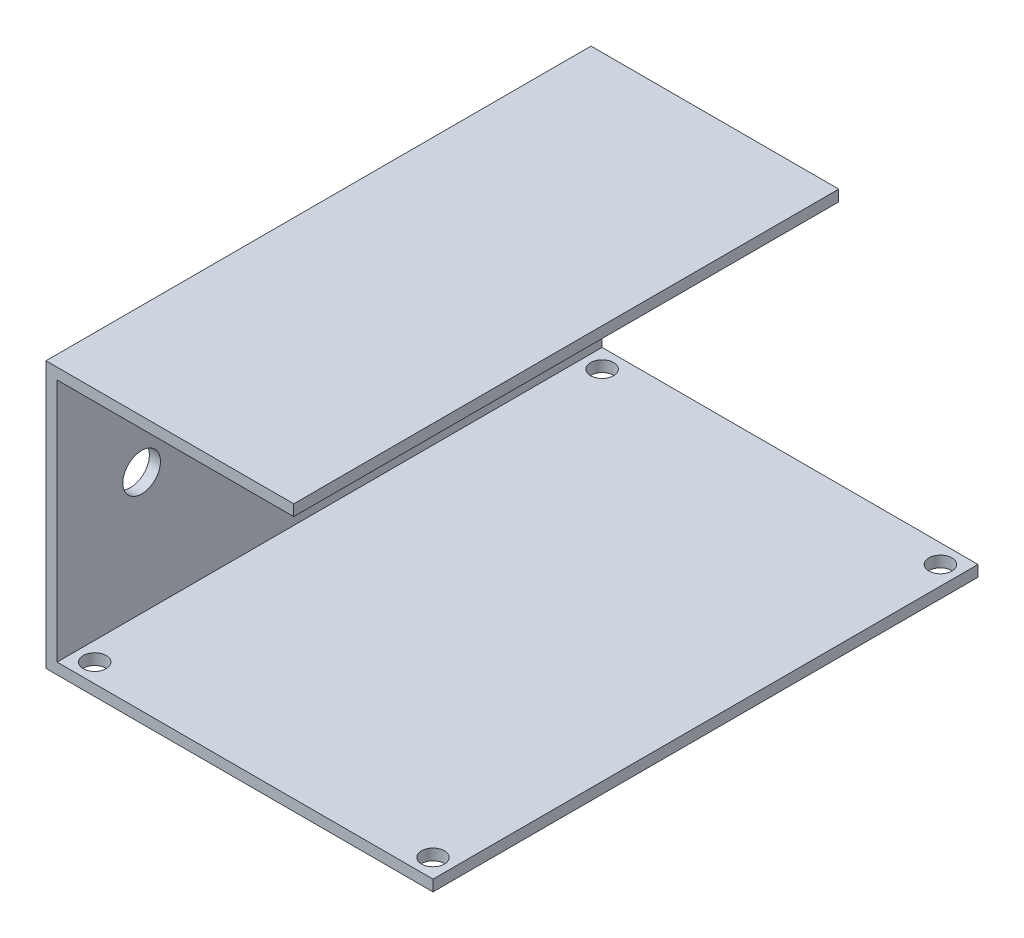
SolidWorks part; units mm, degrees
ref_plane "前视基准面" through (0, 0, 0) normal (0, 0, 1) x (1, 0, 0)
ref_plane "上视基准面" through (0, 0, 0) normal (0, 1, 0) x (1, 0, 0)
ref_plane "右视基准面" through (0, 0, 0) normal (1, 0, 0) x (0, 0, -1)
other "Configuration Table"
sketch "草图1" plane through (0, 0, 0) normal (0, 1, 0) x (1, 0, 0)
  line L1 (22.86, -34.29) -> (-22.86, -34.29) construction
  line L2 (22.86, -34.29) -> (22.86, 34.29) construction
  line L3 (22.86, 34.29) -> (-22.86, 34.29) construction
  line L4 (-22.86, -34.29) -> (-22.86, 34.29) construction
  line L5 (22.86, -34.29) -> (-22.86, 34.29) construction
  line L6 (22.86, 34.29) -> (-22.86, -34.29) construction
  line L7 (25.4, -36.83) -> (-25.4, -36.83)
  line L8 (25.4, -36.83) -> (25.4, 36.83)
  line L9 (25.4, 36.83) -> (-25.4, 36.83)
  line L10 (-25.4, -36.83) -> (-25.4, 36.83)
  line L11 (25.4, -36.83) -> (-25.4, 36.83) construction
  line L12 (25.4, 36.83) -> (-25.4, -36.83) construction
  circle A0 centre (-22.86, 34.29) radius 1.55
  circle A1 centre (22.86, 34.29) radius 1.55
  circle A2 centre (22.86, -34.29) radius 1.55
  circle A3 centre (-22.86, -34.29) radius 1.55
  point P0 (0, 0)
  point P10 (0, 0)
  dimension "D3" = 3.1
  dimension "D4" = 3.1
  dimension "D5" = 3.1
  dimension "D6" = 3.1
  dimension "D1" = 34.29
  dimension "D2" = 22.86
  dimension "D7" = 25.4
  dimension "D8" = 36.83
extrude "凸台-拉伸1" add sketch "草图1" along normal blind 1.5
sketch "草图2" plane through (-25.4, 0, 0) normal (-1, 0, 0) x (0, 0, 1)
  line L1 (-36.83, 1.5) -> (36.83, 1.5)
  line L2 (-36.83, 1.5) -> (-36.83, 0)
  line L3 (-36.83, 0) -> (36.83, 0)
  line L4 (36.83, 1.5) -> (36.83, 0)
extrude "凸台-拉伸2" add sketch "草图2" along normal blind 1.5
sketch "草图3" plane through (0, 1.5, 0) normal (0, 1, 0) x (1, 0, 0)
  line L0 (-26.9, -36.83) -> (25.4, -36.83) construction
  line L1 (-26.9, 36.83) -> (-25.4, 36.83)
  line L2 (-26.9, 36.83) -> (-26.9, -36.83)
  line L3 (-26.9, -36.83) -> (-25.4, -36.83)
  line L4 (-25.4, 36.83) -> (-25.4, -36.83)
  dimension "D1" = 1.5
extrude "凸台-拉伸3" add sketch "草图3" along normal blind 33.02
sketch "草图4" plane through (-25.4, 0, 0) normal (1, 0, 0) x (0, 0, -1)
  line L0 (-36.83, 34.52) -> (36.83, 1.5) construction
  line L1 (-36.83, 1.5) -> (36.83, 34.52) construction
  line L2 (-36.83, 1.5) -> (36.83, 1.5) construction
  line L3 (-36.83, 1.5) -> (36.83, 1.5) construction
  circle A0 centre (0, 18.01) radius 5.334
  circle A1 centre (12.7, 18.01) radius 2.54
  circle A2 centre (25.4, 18.01) radius 2.54
  circle A3 centre (-12.7, 18.01) radius 2.54
  circle A4 centre (-25.4, 18.01) radius 2.54
  dimension "D1" = 10.668
  dimension "D4" = 5.08
  dimension "D5" = 5.08
  dimension "D10" = 5.08
  dimension "D11" = 5.08
  dimension "D2" = 12.7
  dimension "D3" = 12.7
  dimension "D6" = 16.51
  dimension "D7" = 16.51
  dimension "D8" = 12.7
  dimension "D9" = 12.7
  dimension "D12" = 16.51
  dimension "D13" = 16.51
extrude "切除-拉伸1" cut sketch "草图4" against normal blind 33.02
sketch "草图6" plane through (0, 34.52, 0) normal (0, 1, 0) x (1, 0, 0)
  line L1 (-26.9, 36.83) -> (-25.4, 36.83)
  line L2 (-26.9, 36.83) -> (-26.9, -36.83)
  line L3 (-26.9, -36.83) -> (-25.4, -36.83)
  line L4 (-25.4, 36.83) -> (-25.4, -36.83)
extrude "凸台-拉伸4" add sketch "草图6" along normal blind 1.5
sketch "草图7" plane through (-25.4, 0, 0) normal (1, 0, 0) x (0, 0, -1)
  line L0 (36.83, 36.02) -> (36.83, 1.5) construction
  line L1 (-36.83, 36.02) -> (36.83, 36.02)
  line L2 (-36.83, 36.02) -> (-36.83, 34.52)
  line L3 (-36.83, 34.52) -> (36.83, 34.52)
  line L4 (36.83, 36.02) -> (36.83, 34.52)
  dimension "D1" = 1.5
extrude "凸台-拉伸5" add sketch "草图7" along normal blind 31.98
